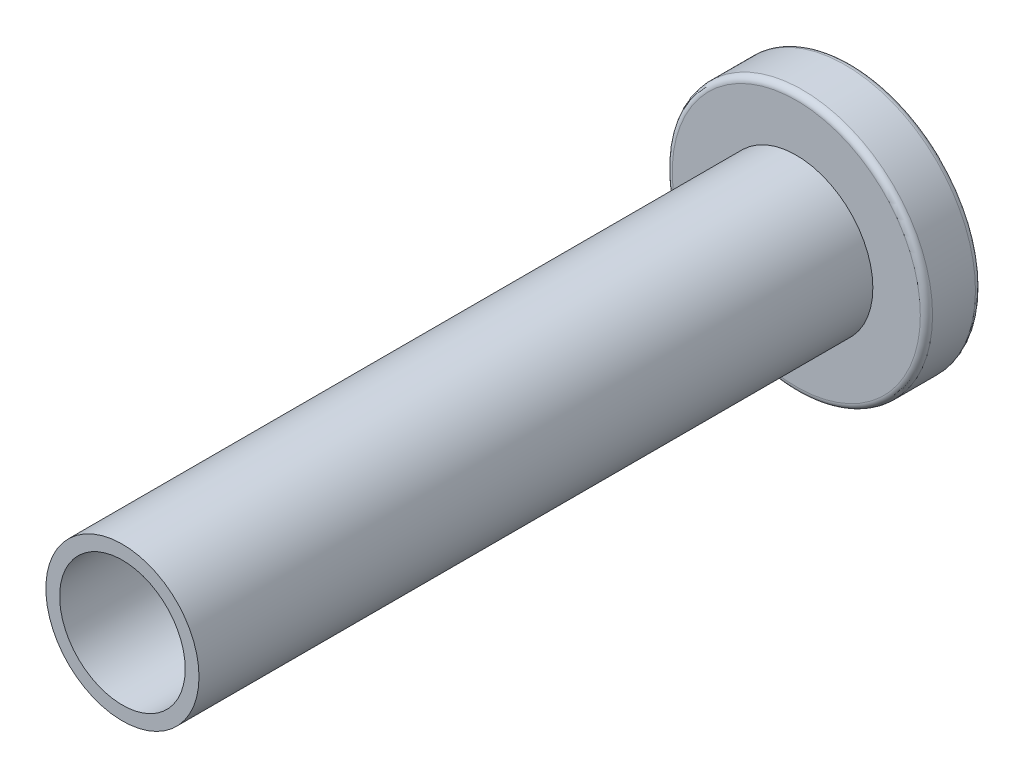
SolidWorks part; units mm, degrees
material "AISI 304"
ref_plane "前视基准面" through (0, 0, 0) normal (0, 0, 1) x (1, 0, 0)
ref_plane "上视基准面" through (0, 0, 0) normal (0, 1, 0) x (1, 0, 0)
ref_plane "右视基准面" through (0, 0, 0) normal (1, 0, 0) x (0, 0, -1)
other "Configuration Table"
sketch "草图1" plane through (0, 0, 0) normal (0, 0, 1) x (1, 0, 0)
  circle A0 centre (0, 0) radius 4.25
  dimension "D1" = 8.5
extrude "凸台-拉伸1" add sketch "草图1" along normal blind 1.8
sketch "草图2" plane through (0, 0, 1.8) normal (0, 0, 1) x (1, 0, 0)
  circle A0 centre (0, 0) radius 2.5
  circle A1 centre (0, 0) radius 2.05
  dimension "D1" = 5
  dimension "D2" = 4.1
extrude "凸台-拉伸2" add sketch "草图2" along normal blind 22
fillet "圆角1" radius 0.2 2 edges at (4.25, 0, 0) (4.25, 0, 1.8)
sketch "草图3" plane through (0, 0, 0) normal (0, 0, -1) x (-1, 0, 0)
  line L0 (0, 0) -> (1.4434, 0) construction
  line L1 (1.4434, 0) -> (0.7217, 1.25)
  line L2 (0.7217, 1.25) -> (-0.7217, 1.25)
  line L3 (-0.7217, 1.25) -> (-1.4434, 0)
  line L4 (-1.4434, 0) -> (-0.7217, -1.25)
  line L5 (-0.7217, -1.25) -> (0.7217, -1.25)
  line L6 (0.7217, -1.25) -> (1.4434, 0)
  circle A0 centre (0, 0) radius 1.25 construction
  dimension "D1" = 2.5
extrude "切除-拉伸1" cut sketch "草图3" against normal blind 1.5
